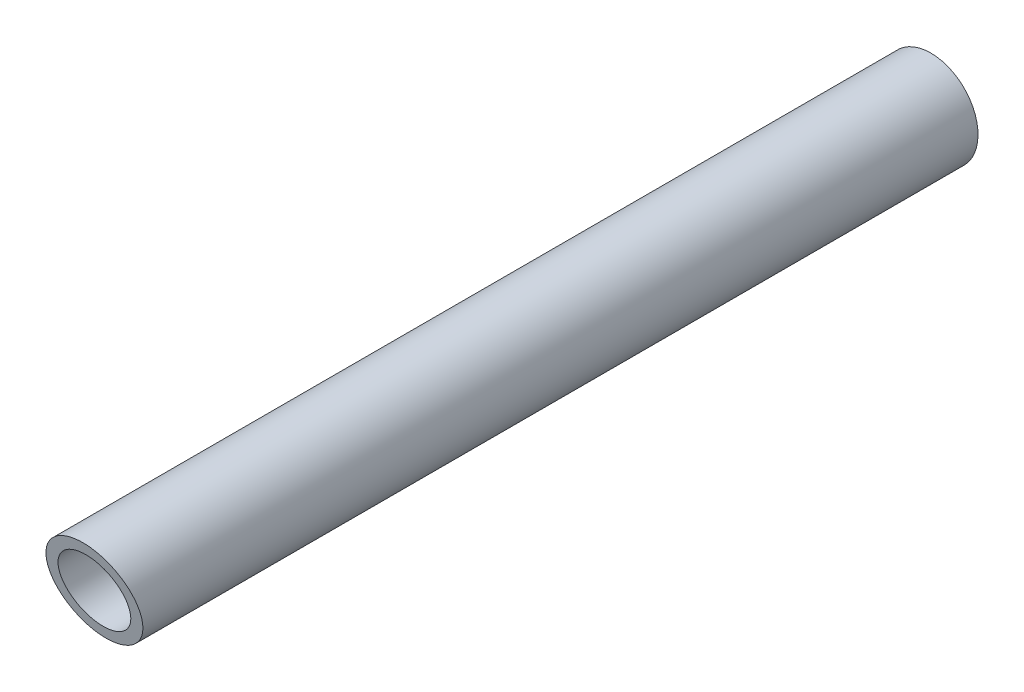
SolidWorks part; units mm, degrees
ref_plane "Front Plane" through (0, 0, 0) normal (0, 0, 1) x (1, 0, 0)
ref_plane "Top Plane" through (0, 0, 0) normal (0, 1, 0) x (1, 0, 0)
ref_plane "Right Plane" through (0, 0, 0) normal (1, 0, 0) x (0, 0, -1)
sketch "Sketch1" plane through (0, 0, 0) normal (0, 0, 1) x (1, 0, 0)
  line L0 (12.7, 0) -> (9.525, 0) construction
  line L1 (-12.7, 0) -> (12.7, 0) construction
  dimension "OD" = 25.4
  dimension "Wall Thickness" = 3.175
sketch "Sketch2" plane through (0, 0, 0) normal (1, 0, 0) x (0, 0, -1)
  line L0 (114.3, 0) -> (-114.3, 0)
  point P4 (0, 0)
  dimension "Length" = 228.6
sketch "Sketch3" plane through (0, 0, 0) normal (0, 0, 1) x (1, 0, 0)
  circle A0 centre (0, 0) radius 12.7
  circle A1 centre (0, 0) radius 9.525
extrude "Boss-Extrude1" add sketch "Sketch3" along normal up to vertex (114.3 mm away) and the other way up to vertex (114.3 mm away) up to point (0, 0, 114.3) other way up to point (0, 0, -114.3)
sketch "Sketch4" plane through (0, 0, 114.3) normal (0, 0, 1) x (1, 0, 0)
  line L0 (-12.7, 0) -> (12.7, 0) construction
  line L2 (-12.7, -12.7) -> (12.7, -12.7)
  line L3 (-12.7, -12.7) -> (-12.7, 12.7)
  line L4 (-12.7, 12.7) -> (12.7, 12.7)
  line L5 (12.7, -12.7) -> (12.7, 12.7)
  line L6 (-12.7, -12.7) -> (12.7, 12.7) construction
  line L7 (-12.7, 12.7) -> (12.7, -12.7) construction
  circle A0 centre (0, 0) radius 12.7 construction
  point P5 (0, 0)
  dimension "D1" = 25.4
ref_plane "Plane1" through (0, -25.6581, 104.9195) normal (0, -0.2376, 0.9714) x (1, 0, 0)
other "SurfaceCut1"
ref_plane "Plane2" through (12.7, 0, 0) normal (1, 0, 0) x (0, 0, -1)
sketch "Sketch5" plane through (0, 0, -114.3) normal (0, 0, -1) x (-1, 0, 0)
  line L0 (0, -12.7) -> (-25.4, -12.7) construction
  line L1 (-25.4, -12.7) -> (-9.2129, -8.7414) construction
  line L2 (-9.2129, -8.7414) -> (9.2129, -8.7414) construction
  circle A0 centre (0, 0) radius 12.7 construction
  dimension "D1" = 13.742
  dimension "D2" = 25.4
ref_plane "Plane3" through (0, -34.6229, -8.4671) normal (0, 0.9714, 0.2376) x (-1, 0, 0)
other "SurfaceCut2"
